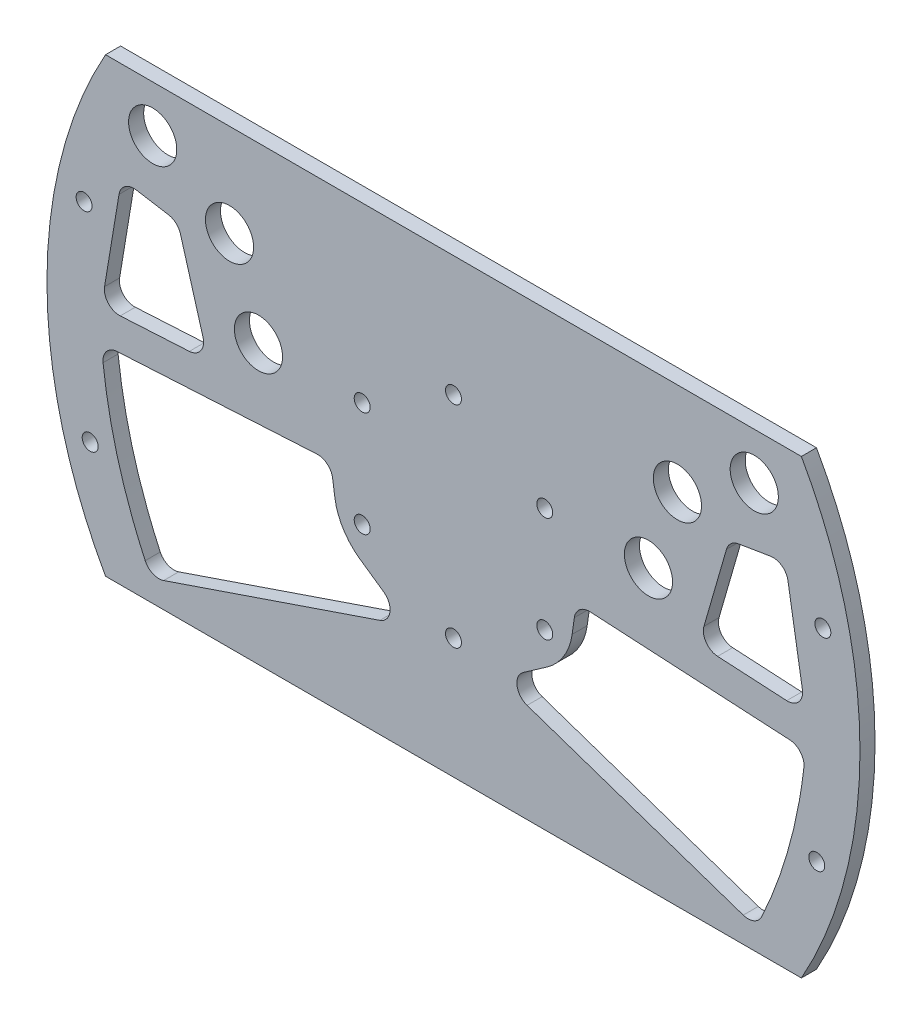
SolidWorks part; units mm, degrees
material "6061 Alloy"
ref_plane "Front Plane" through (0, 0, 0) normal (0, 0, 1) x (1, 0, 0)
ref_plane "Top Plane" through (0, 0, 0) normal (0, 1, 0) x (1, 0, 0)
ref_plane "Right Plane" through (0, 0, 0) normal (1, 0, 0) x (0, 0, -1)
sketch "Sketch4" plane through (0, 0, 0) normal (0, 0, 1) x (1, 0, 0)
  line L0 (864.0761, -503.3021) -> (0, 0) construction
  line L1 (0, 0) -> (0, 35) construction
  line L2 (-115.5383, -75) -> (115.5383, -75)
  line L3 (0, 0) -> (305.5429, 174.8466) construction
  line L6 (-115.5383, 75) -> (115.5383, 75)
  line L8 (96.2214, -66.5692) -> (24.4434, -42.1315)
  line L9 (23.1942, -33.2975) -> (31.0448, -27.8209)
  line L11 (39.4015, -14.2432) -> (40.1425, -9.0507)
  line L12 (45.369, -4.7647) -> (111.6869, -8.4394)
  line L18 (115.8696, 8.1318) -> (111.0707, 37.071)
  line L19 (105.3201, 41.1856) -> (94.6541, 39.4169)
  line L20 (90.6687, 35.8725) -> (83.1835, 9.9738)
  line L21 (87.7103, 3.5932) -> (110.6604, 2.3215)
  line L22 (-96.2214, -66.5692) -> (-24.4434, -42.1315)
  line L23 (-23.1942, -33.2975) -> (-31.0448, -27.8209)
  line L24 (-39.4015, -14.2432) -> (-40.1425, -9.0507)
  line L25 (-45.369, -4.7647) -> (-111.6869, -8.4394)
  line L26 (-90.6687, 35.8725) -> (-83.1835, 9.9738)
  line L27 (-105.3201, 41.1856) -> (-94.6541, 39.4169)
  line L28 (-115.8696, 8.1318) -> (-111.0707, 37.071)
  line L29 (-87.7103, 3.5932) -> (-110.6604, 2.3215)
  circle A0 centre (0, 35) radius 2.65
  circle A1 centre (30.3109, 17.5) radius 2.65
  circle A2 centre (30.3109, -17.5) radius 2.65
  circle A3 centre (0, -35) radius 2.65
  circle A4 centre (-30.3109, -17.5) radius 2.65
  circle A5 centre (-30.3109, 17.5) radius 2.65
  arc A9 (31.0448, -27.8209) -> (39.4015, -14.2432) centre (19.6021, -11.4177) ccw
  arc A11 (24.4434, -42.1315) -> (23.1942, -33.2975) centre (26.0548, -37.3983) cw
  arc A12 (40.1425, -9.0507) -> (45.369, -4.7647) centre (45.0924, -9.7571) cw
  arc A13 (111.6869, -8.4394) -> (116.3777, -14.0021) centre (111.4103, -13.4318) cw
  arc A14 (96.2214, -66.5692) -> (102.371, -63.9349) centre (97.8329, -61.836) ccw
  arc A15 (115.8696, 8.1318) -> (110.6604, 2.3215) centre (110.937, 7.3139) cw
  arc A16 (111.0707, 37.071) -> (105.3201, 41.1856) centre (106.138, 36.253) ccw
  arc A17 (94.6541, 39.4169) -> (90.6687, 35.8725) centre (95.4721, 34.4842) ccw
  arc A18 (83.1835, 9.9738) -> (87.7103, 3.5932) centre (87.9869, 8.5855) ccw
  circle A19 centre (64.752, 17.5) radius 8
  circle A20 centre (74.3747, 44.1855) radius 8
  circle A21 centre (99.8885, 59.5161) radius 8
  arc A22 (-24.4434, -42.1315) -> (-23.1942, -33.2975) centre (-26.0548, -37.3983) ccw
  arc A23 (-31.0448, -27.8209) -> (-39.4015, -14.2432) centre (-19.6021, -11.4177) cw
  arc A24 (-40.1425, -9.0507) -> (-45.369, -4.7647) centre (-45.0924, -9.7571) ccw
  arc A25 (-111.6869, -8.4394) -> (-116.3777, -14.0021) centre (-111.4103, -13.4318) ccw
  arc A26 (-96.2214, -66.5692) -> (-102.371, -63.9349) centre (-97.8329, -61.836) cw
  arc A27 (-94.6541, 39.4169) -> (-90.6687, 35.8725) centre (-95.4721, 34.4842) cw
  arc A28 (-111.0707, 37.071) -> (-105.3201, 41.1856) centre (-106.138, 36.253) cw
  arc A29 (-115.8696, 8.1318) -> (-110.6604, 2.3215) centre (-110.937, 7.3139) ccw
  arc A30 (-83.1835, 9.9738) -> (-87.7103, 3.5932) centre (-87.9869, 8.5855) cw
  circle A31 centre (-99.8885, 59.5161) radius 8
  circle A32 centre (-74.3747, 44.1855) radius 8
  circle A33 centre (-64.752, 17.5) radius 8
  circle A34 centre (120.644, -38.9483) radius 2.65
  circle A35 centre (122.6649, 29.2011) radius 2.65
  circle A36 centre (-122.6649, 29.2011) radius 2.65
  circle A37 centre (-120.644, -38.9483) radius 2.65
  ellipse E0 centre (0, 0) end of major axis (0, -145) minor radius 135 (-115.5383, 75) -> (-115.5383, -75) ccw
  ellipse E1 centre (0, 0) end of major axis (0, -145) minor radius 135 (115.5383, -75) -> (115.5383, 75) ccw
  spline S0 degree 3 poles (116.3777, -14.0021) (115.2208, -24.0769) (111.676, -41.0554) (105.466, -57.2433) (102.371, -63.9349) knots 0.084665 0.084665 0.084665 0.084665 0.572063 0.927684 0.927684 0.927684 0.927684
  spline S1 degree 3 poles (-116.3777, -14.0021) (-115.2208, -24.0769) (-111.676, -41.0554) (-105.466, -57.2433) (-102.371, -63.9349) knots 0.084665 0.084665 0.084665 0.084665 0.572063 0.927684 0.927684 0.927684 0.927684
  point P43 (0, -45)
  point P48 (70, -70)
  point P51 (-70, -70)
  point P74 (15.0937, -38.9483)
  point P77 (40.7904, -4.511)
  point P84 (116.8904, 1.9763)
  point P87 (110.2527, 42.0036)
  point P90 (91.544, 38.9011)
  point P93 (81.4398, 3.9406)
  dimension "D1" = 60
  dimension "D2" = 75
  dimension "D6" = 5.3
  dimension "D7" = 70
  dimension "D18" = 5
  dimension "D19" = 5
  dimension "D20" = 5
  dimension "D21" = 5
  dimension "D17" = 5
  dimension "D22" = 5
  dimension "D23" = 5
  dimension "D24" = 16
  dimension "D25" = 16
  dimension "D15" = 20
  dimension "D16" = 5
  dimension "D26" = 16
  dimension "D3" = 75
  dimension "D4" = 145
  dimension "D5" = 135
  dimension "D8" = 35
  dimension "D9" = 6
  dimension "D10" = 140
  dimension "D11" = 25
extrude "Boss-Extrude1" add sketch "Sketch4" along normal blind 5
